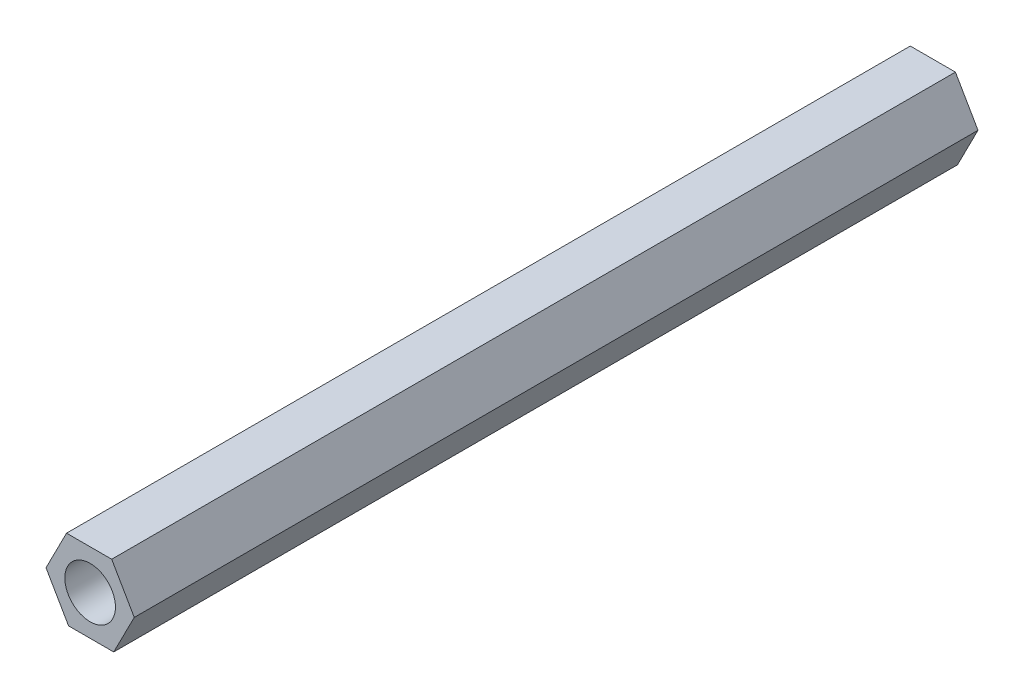
SolidWorks part; units mm, degrees
ref_plane "前视基准面" through (0, 0, 0) normal (0, 0, 1) x (1, 0, 0)
ref_plane "上视基准面" through (0, 0, 0) normal (0, 1, 0) x (1, 0, 0)
ref_plane "右视基准面" through (0, 0, 0) normal (1, 0, 0) x (0, 0, -1)
sketch "草图1" plane through (0, 0, 0) normal (0, 0, 1) x (1, 0, 0)
  line L0 (0, 0) -> (2.6757, 0)
  line L1 (2.6757, 0) -> (4.0136, -2.3172)
  line L2 (4.0136, -2.3172) -> (2.7962, -4.7)
  line L3 (2.7962, -4.7) -> (0.1205, -4.7)
  line L4 (0.1205, -4.7) -> (-1.2173, -2.3828)
  line L5 (-1.2173, -2.3828) -> (0, 0)
  point P0 (0, 0)
  point P7 (0, 0)
  point P8 (0, 0)
  dimension "D1" = 120
  dimension "D2" = 4.7
  dimension "D3" = 5.2309
sketch "草图2" plane through (0, 0, 0) normal (0, 0, 1) x (1, 0, 0)
  line L0 (2.6757, 0) -> (0.1205, -4.7) construction
  line L1 (0, 0) -> (2.7968, -4.6989) construction
  line L2 (4.0136, -2.3172) -> (2.7962, -4.7) construction
  circle A0 centre (1.3981, -2.35) radius 1.5
  point P6 (0, 0)
  point P7 (0, 0)
  point P13 (2.7968, -4.7)
  point P14 (1.3981, -2.35)
  dimension "D1" = 3
extrude "凸台-拉伸1" add sketch "草图1" along normal blind 50
extrude "切除-拉伸1" cut sketch "草图2" along normal blind 50
cosmetic thread "装饰螺纹线1" parameters "D2"=4
